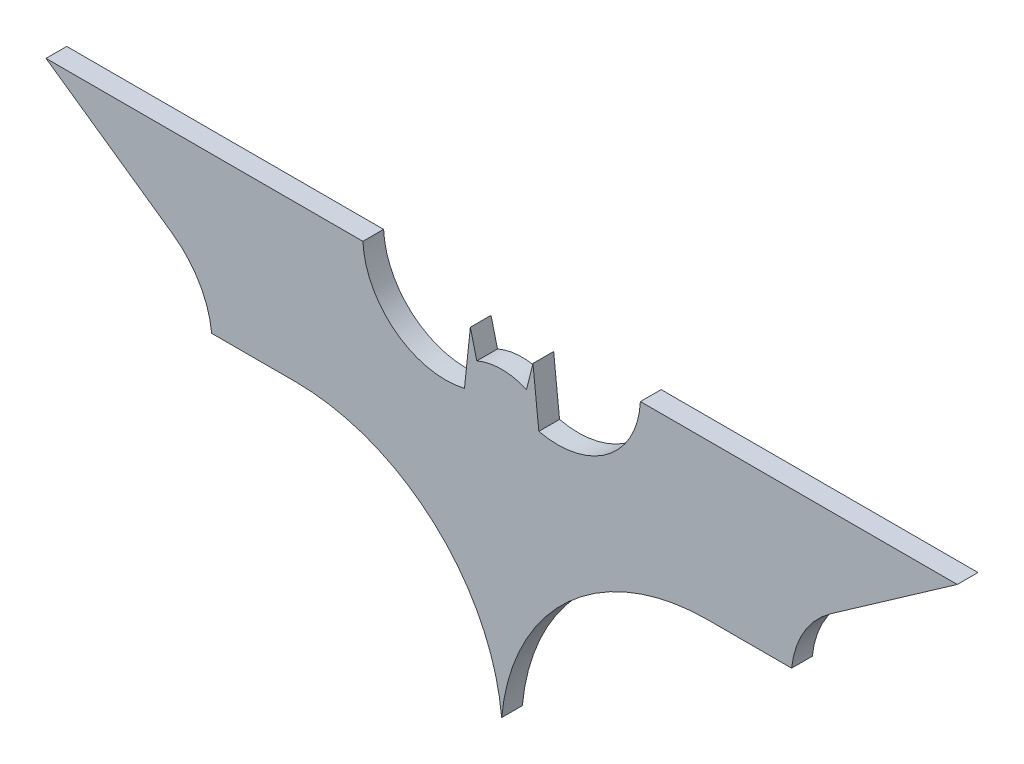
SolidWorks part; units mm, degrees
ref_plane "Front Plane" through (0, 0, 0) normal (0, 0, 1) x (1, 0, 0)
ref_plane "Top Plane" through (0, 0, 0) normal (0, 1, 0) x (1, 0, 0)
ref_plane "Right Plane" through (0, 0, 0) normal (1, 0, 0) x (0, 0, -1)
sketch "Sketch1" plane through (0, 0, 0) normal (0, 0, 1) x (1, 0, 0)
  line L0 (0, 145.9429) -> (0, -145.9429) construction
  line L1 (67, 50) -> (220, 50)
  line L2 (-67, 50) -> (-220, 50)
  line L3 (17.9555, 13) -> (15.1177, 40)
  line L4 (15.1177, 40) -> (12, 27.4955)
  line L5 (-15.1177, 40) -> (-12, 27.4955)
  line L6 (-17.9555, 13) -> (-15.1177, 40)
  line L7 (220, 50) -> (158.9525, 7.2541)
  line L8 (-220, 50) -> (-158.9525, 7.2541)
  line L9 (-140, -25) -> (-99.5632, -25)
  line L10 (140, -25) -> (99.5632, -25)
  arc A0 (67, 50) -> (17.9555, 13) centre (27.0477, 51.953) cw
  arc A1 (-67, 50) -> (-17.9555, 13) centre (-27.0477, 51.953) ccw
  arc A2 (12, 27.4955) -> (-12, 27.4955) centre (0, 0) ccw
  arc A3 (158.9525, 7.2541) -> (140, -25) centre (184.7635, -29.6077) ccw
  arc A4 (-99.5632, -25) -> (0, -115.6638) centre (-99.5632, -125) cw
  arc A5 (99.5632, -25) -> (0, -115.6638) centre (99.5632, -125) ccw
  arc A6 (-158.9525, 7.2541) -> (-140, -25) centre (-184.7635, -29.6077) cw
  dimension "D2" = 40
  dimension "D5" = 30
  dimension "D10" = 220
  dimension "D12" = 45
  dimension "D13" = 100
  dimension "D1" = 134
  dimension "D3" = 84
  dimension "D4" = 160
  dimension "D6" = 50
  dimension "D7" = 24
  dimension "D8" = 37
  dimension "D9" = 10
  dimension "D11" = 35
  dimension "D14" = 140
  dimension "D15" = 75
  dimension "D16" = 140
  dimension "D17" = 99.5632
extrude "Boss-Extrude1" add sketch "Sketch1" along normal blind 10
